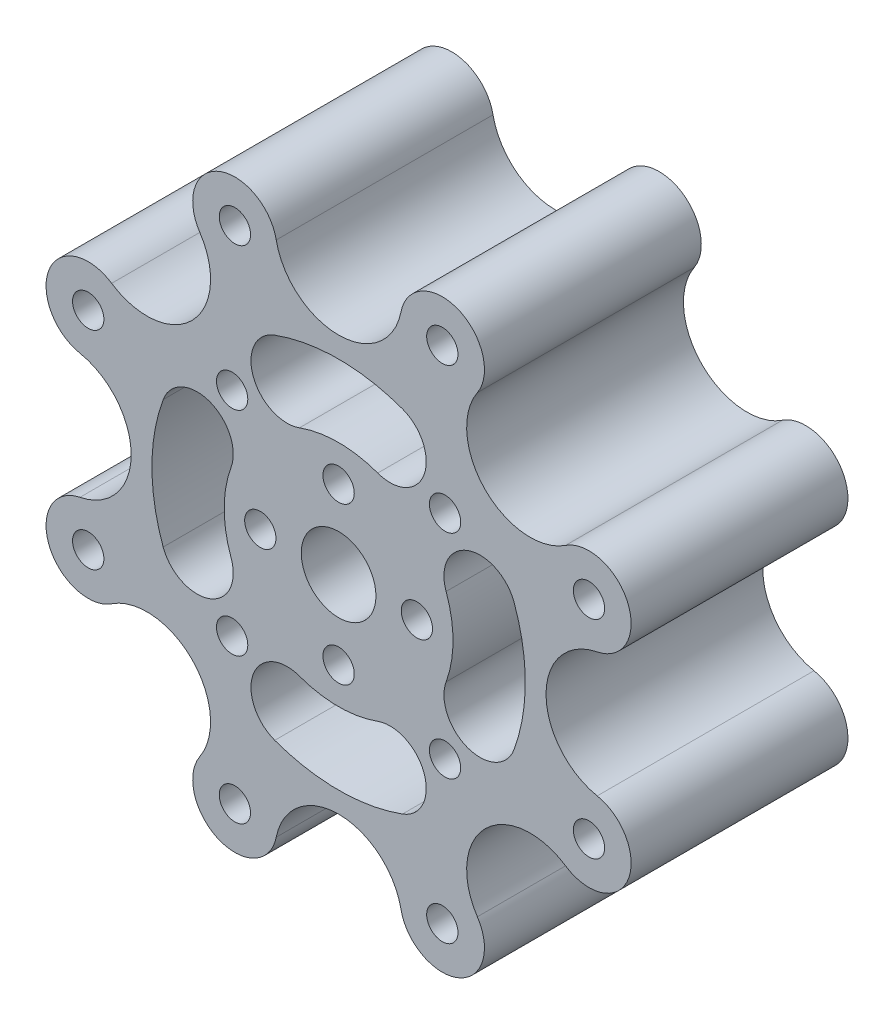
SolidWorks part; units mm, degrees
material "5052-H34"
ref_plane "正面" through (0, 0, 0) normal (0, 0, 1) x (1, 0, 0)
ref_plane "平面" through (0, 0, 0) normal (0, 1, 0) x (1, 0, 0)
ref_plane "右側面" through (0, 0, 0) normal (1, 0, 0) x (0, 0, -1)
sketch "ｽｹｯﾁ1" plane through (0, 0, 0) normal (0, 0, 1) x (1, 0, 0)
  line L0 (0, 27.5) -> (0, 0) construction
  line L1 (0, 0) -> (8.6104, 20.7873) construction
  line L3 (-8.8388, 8.8388) -> (8.8388, 8.8388) construction
  line L4 (-8.8388, 8.8388) -> (-8.8388, -8.8388) construction
  line L5 (-8.8388, -8.8388) -> (8.8388, -8.8388) construction
  line L6 (8.8388, 8.8388) -> (8.8388, -8.8388) construction
  line L7 (-8.8388, 8.8388) -> (8.8388, -8.8388) construction
  line L8 (-8.8388, -8.8388) -> (8.8388, 8.8388) construction
  circle A0 centre (0, 0) radius 27.5
  circle A1 centre (0, 0) radius 22.5 construction
  circle A2 centre (8.6104, 20.7873) radius 1.3
  arc A3 (11.5205, 18.8428) -> (5.1776, 21.4701) centre (8.6104, 20.7873) ccw
  arc A4 (-5.1776, 21.4701) -> (5.1776, 21.4701) centre (0, 22.5) ccw
  circle A5 centre (20.7873, 8.6104) radius 1.3
  circle A6 centre (20.7873, -8.6104) radius 1.3
  circle A7 centre (8.6104, -20.7873) radius 1.3
  circle A8 centre (-8.6104, -20.7873) radius 1.3
  circle A9 centre (-20.7873, -8.6104) radius 1.3
  circle A10 centre (-20.7873, 8.6104) radius 1.3
  circle A11 centre (-8.6104, 20.7873) radius 1.3
  arc A12 (-5.2824, 21.8711) -> (-11.73, 19.2005) centre (-8.6104, 20.7873) ccw construction
  arc A13 (5.2426, 21.8807) -> (0, 27.7791) centre (0, 22.5) ccw construction
  arc A14 (0, 27.7791) -> (-5.2426, 21.8807) centre (0, 22.5) ccw construction
  arc A15 (5.1776, 21.4701) -> (7.271, 17.5537) centre (8.6104, 20.7873) ccw construction
  arc A16 (19.1791, 11.7649) -> (11.5205, 18.8428) centre (15.9099, 15.9099) cw construction
  arc A17 (-5.2426, 21.8807) -> (-5.1776, 21.4701) centre (0, 22.5) ccw construction
  arc A18 (-5.1776, 21.4701) -> (-5.2824, 21.8711) centre (-8.6104, 20.7873) ccw construction
  arc A19 (5.1776, 21.4701) -> (5.2426, 21.8807) centre (0, 22.5) ccw construction
  arc A20 (7.271, 17.5537) -> (11.5205, 18.8428) centre (8.6104, 20.7873) ccw construction
  arc A21 (11.5205, 18.8428) -> (11.7649, 19.1791) centre (15.9099, 15.9099) cw construction
  arc A22 (-11.73, 19.2005) -> (-5.1776, 21.4701) centre (-8.6104, 20.7873) ccw construction
  arc A23 (11.5205, 18.8428) -> (18.8428, 11.5205) centre (15.9099, 15.9099) ccw
  arc A24 (21.4701, 5.1776) -> (18.8428, 11.5205) centre (20.7873, 8.6104) ccw
  arc A25 (21.4701, 5.1776) -> (21.4701, -5.1776) centre (22.5, 0) ccw
  arc A26 (18.8428, -11.5205) -> (21.4701, -5.1776) centre (20.7873, -8.6104) ccw
  arc A27 (18.8428, -11.5205) -> (11.5205, -18.8428) centre (15.9099, -15.9099) ccw
  arc A28 (5.1776, -21.4701) -> (11.5205, -18.8428) centre (8.6104, -20.7873) ccw
  arc A29 (5.1776, -21.4701) -> (-5.1776, -21.4701) centre (0, -22.5) ccw
  arc A30 (-11.5205, -18.8428) -> (-5.1776, -21.4701) centre (-8.6104, -20.7873) ccw
  arc A31 (-11.5205, -18.8428) -> (-18.8428, -11.5205) centre (-15.9099, -15.9099) ccw
  arc A32 (-21.4701, -5.1776) -> (-18.8428, -11.5205) centre (-20.7873, -8.6104) ccw
  arc A33 (-21.4701, -5.1776) -> (-21.4701, 5.1776) centre (-22.5, 0) ccw
  arc A34 (-18.8428, 11.5205) -> (-21.4701, 5.1776) centre (-20.7873, 8.6104) ccw
  arc A35 (-18.8428, 11.5205) -> (-11.5205, 18.8428) centre (-15.9099, 15.9099) ccw
  arc A36 (-5.1776, 21.4701) -> (-11.5205, 18.8428) centre (-8.6104, 20.7873) ccw
  circle A37 centre (8.8388, 8.8388) radius 1.3
  circle A38 centre (8.8388, -8.8388) radius 1.3
  circle A39 centre (-8.8388, -8.8388) radius 1.3
  circle A40 centre (-8.8388, 8.8388) radius 1.3
  circle A41 centre (0, 0) radius 6.5 construction
  circle A42 centre (0, 6.5) radius 1.3
  circle A43 centre (6.5, 0) radius 1.3
  circle A44 centre (0, -6.5) radius 1.3
  circle A45 centre (-6.5, 0) radius 1.3
  circle A46 centre (0, 0) radius 12.5 construction
  circle A47 centre (0, 12.5) radius 3
  circle A48 centre (12.5, 0) radius 3
  circle A49 centre (0, -12.5) radius 3
  circle A50 centre (-12.5, 0) radius 3
  circle A51 centre (0, 0) radius 3.1
  dimension "D1" = 55
  dimension "D2" = 45
  dimension "D4" = 2.6
  dimension "D6" = 2.6
  dimension "D7" = 13
  dimension "D9" = 6
  dimension "D10" = 25
  dimension "D12" = 3.5
  dimension "D13" = 6.2
  dimension "D3" = 22.5
  dimension "D5" = 25
  dimension "D11" = 8
  dimension "D8" = 4
extrude "ﾎﾞｽ - 押し出し1" add sketch "ｽｹｯﾁ1" along normal blind 18 contours A4 A36 A35 A34 A33 A32 A31 A30 A29 A28 A27 A26 A25 A24 A23 A3 A50 A49 A48 A47 A45 A44 A43 A42 A40 A39 A38 A37 A2 A5 A6 A7 A8
sketch "ｽｹｯﾁ2" plane through (0, 0, 18) normal (0, 0, 1) x (1, 0, 0)
  line L0 (0, 0) -> (4.2753, 11.7462) construction
  line L1 (0, 12.5) -> (0, 0) construction
  arc A0 (3.2492, 8.9271) -> (-3.2492, 8.9271) centre (0, 0) ccw
  circle A1 centre (0, 12.5) radius 3 construction
  circle A2 centre (0, 12.5) radius 3
  arc A3 (5.3013, 14.5652) -> (-5.3013, 14.5652) centre (0, 0) ccw
  arc A4 (3.2492, 8.9271) -> (5.3013, 14.5652) centre (4.2753, 11.7462) ccw
  arc A5 (-3.2492, 8.9271) -> (-5.3013, 14.5652) centre (-4.2753, 11.7462) cw
  arc A6 (8.9271, 3.2492) -> (14.5652, 5.3013) centre (11.7462, 4.2753) cw
  arc A7 (14.5652, -5.3013) -> (14.5652, 5.3013) centre (0, 0) ccw
  arc A8 (8.9271, -3.2492) -> (8.9271, 3.2492) centre (0, 0) ccw
  arc A9 (8.9271, -3.2492) -> (14.5652, -5.3013) centre (11.7462, -4.2753) ccw
  arc A10 (3.2492, -8.9271) -> (5.3013, -14.5652) centre (4.2753, -11.7462) cw
  arc A11 (-5.3013, -14.5652) -> (5.3013, -14.5652) centre (0, 0) ccw
  arc A12 (-3.2492, -8.9271) -> (3.2492, -8.9271) centre (0, 0) ccw
  arc A13 (-3.2492, -8.9271) -> (-5.3013, -14.5652) centre (-4.2753, -11.7462) ccw
  arc A14 (-8.9271, -3.2492) -> (-14.5652, -5.3013) centre (-11.7462, -4.2753) cw
  arc A15 (-14.5652, 5.3013) -> (-14.5652, -5.3013) centre (0, 0) ccw
  arc A16 (-8.9271, 3.2492) -> (-8.9271, -3.2492) centre (0, 0) ccw
  arc A17 (-8.9271, 3.2492) -> (-14.5652, 5.3013) centre (-11.7462, 4.2753) ccw
  circle M9 centre (-12.5, 0) radius 3
  circle M10 centre (0, -12.5) radius 3
  circle M11 centre (12.5, 0) radius 3
  circle M12 centre (0, 12.5) radius 3
  dimension "D1" = 20
  dimension "D2" = 4
extrude "ｶｯﾄ - 押し出し1" cut sketch "ｽｹｯﾁ2" against normal through all contours A16 A17 A15 M9 | A16 A15 A14 M9 | A12 A11 A10 M10 | A12 A13 A11 M10 | A8 A9 A7 M11 | A8 A7 A6 M11 | A0 A4 A3 A2 | A5 A0 A3 M12
